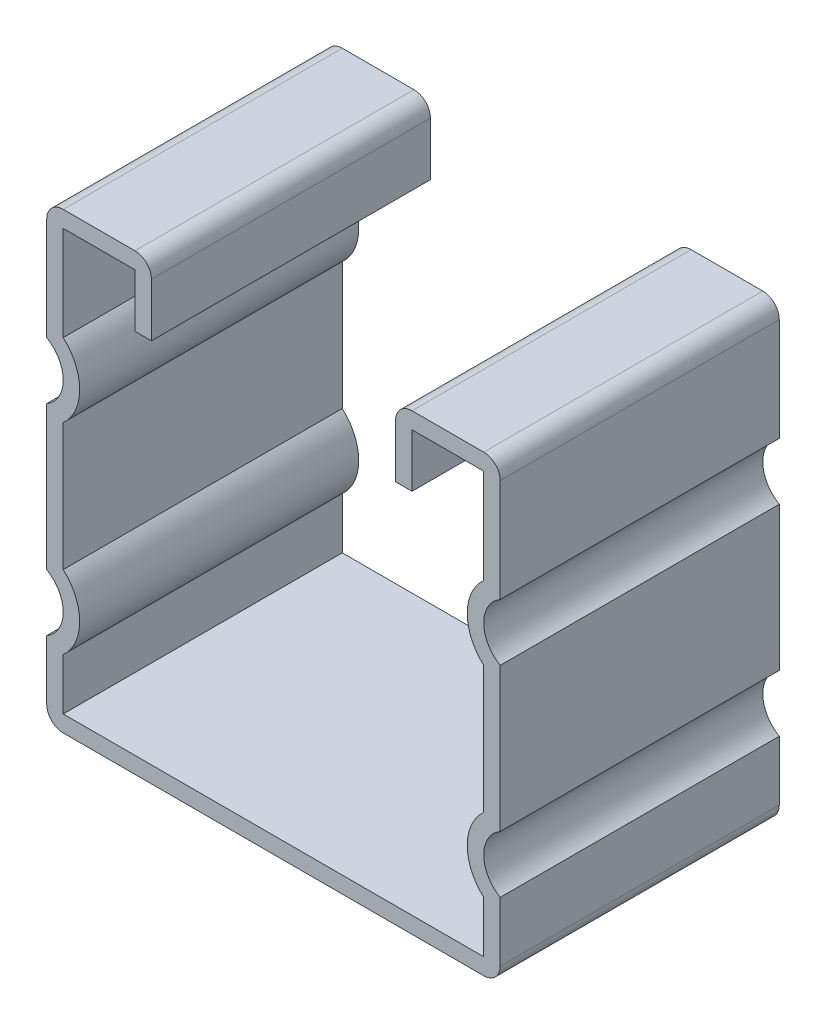
SolidWorks part; units mm, degrees
ref_plane "Plane1" through (0, 0, 0) normal (0, 0, 1) x (1, 0, 0)
ref_plane "Plane2" through (0, 0, 0) normal (0, 1, 0) x (1, 0, 0)
ref_plane "Plane3" through (0, 0, 0) normal (1, 0, 0) x (0, 0, -1)
sketch "Sketch1" plane through (0, 0, 0) normal (0, 0, 1) x (1, 0, 0)
  line L0 (-20.6375, 21.1074) -> (-20.6375, 11.7397)
  line L1 (-20.6375, 6.5483) -> (-20.6375, -6.5483)
  line L2 (-19.1389, -18.669) -> (19.1389, -18.669)
  line L3 (20.6375, -17.1704) -> (20.6375, -11.7397)
  line L4 (20.6375, 11.7397) -> (20.6375, 21.1074)
  line L5 (19.1389, 22.606) -> (12.6111, 22.606)
  line L6 (11.1125, 21.1074) -> (11.1125, 16.256)
  line L7 (-19.1389, 22.606) -> (-12.6111, 22.606)
  line L8 (-11.1125, 21.1074) -> (-11.1125, 16.256)
  line L9 (19.1389, -12.495) -> (19.1389, 12.495) construction
  line L10 (-19.1389, 12.495) -> (-19.1389, -12.495) construction
  line L11 (-12.6111, 21.1074) -> (-12.6111, 16.256)
  line L12 (-19.1389, 21.1074) -> (-12.6111, 21.1074)
  line L13 (-19.1389, 21.1074) -> (-19.1389, 12.495)
  line L14 (-19.1389, 5.793) -> (-19.1389, -5.793)
  line L15 (-19.1389, -17.1704) -> (19.1389, -17.1704)
  line L16 (19.1389, -17.1704) -> (19.1389, -12.495)
  line L17 (19.1389, 12.495) -> (19.1389, 21.1074)
  line L18 (19.1389, 21.1074) -> (12.6111, 21.1074)
  line L19 (12.6111, 21.1074) -> (12.6111, 16.256)
  line L20 (-12.6111, 16.256) -> (-11.1125, 16.256)
  line L21 (11.1125, 16.256) -> (12.6111, 16.256)
  line L22 (-10.16, 0) -> (12.7, 0) construction
  line L23 (-20.6375, -11.7397) -> (-20.6375, -17.1704)
  line L24 (-19.1389, -12.495) -> (-19.1389, -17.1704)
  line L25 (20.6375, -6.5483) -> (20.6375, 6.5483)
  line L26 (19.1389, -5.793) -> (19.1389, 5.793)
  arc A0 (20.6375, 11.7397) -> (20.6375, 6.5483) centre (22.1361, 9.144) ccw
  arc A1 (-20.6375, 6.5483) -> (-20.6375, 11.7397) centre (-22.1361, 9.144) ccw
  arc A2 (-12.6111, 22.606) -> (-11.1125, 21.1074) centre (-12.6111, 21.1074) cw
  arc A3 (-20.6375, 21.1074) -> (-19.1389, 22.606) centre (-19.1389, 21.1074) cw
  arc A4 (-19.1389, -18.669) -> (-20.6375, -17.1704) centre (-19.1389, -17.1704) cw
  arc A5 (20.6375, -17.1704) -> (19.1389, -18.669) centre (19.1389, -17.1704) cw
  arc A6 (19.1389, 22.606) -> (20.6375, 21.1074) centre (19.1389, 21.1074) cw
  arc A7 (11.1125, 21.1074) -> (12.6111, 22.606) centre (12.6111, 21.1074) cw
  arc A8 (-19.1389, 5.793) -> (-19.1389, 12.495) centre (-22.1361, 9.144) ccw
  arc A9 (19.1389, 12.495) -> (19.1389, 5.793) centre (22.1361, 9.144) ccw
  arc A10 (20.6375, -11.7397) -> (20.6375, -6.5483) centre (22.1361, -9.144) cw
  arc A11 (19.1389, -12.495) -> (19.1389, -5.793) centre (22.1361, -9.144) cw
  arc A12 (-19.1389, -5.793) -> (-19.1389, -12.495) centre (-22.1361, -9.144) cw
  arc A13 (-20.6375, -6.5483) -> (-20.6375, -11.7397) centre (-22.1361, -9.144) cw
  dimension "D9" = 2.9972
  dimension "D10" = 2.9972
  dimension "D1" = 20.6375
  dimension "Width" = 41.275
  dimension "base" = 18.669
  dimension "ToeHt" = 22.606
  dimension "D6" = 22.225
  dimension "edge" = 9.525
  dimension "Lip" = 6.35
  dimension "D2" = 9.525
  dimension "gauge" = 1.4986
extrude "Base-Extrude" add sketch "Sketch1" along normal mid plane 25.4
equation "\"D1@Sketch1\" = \"Width@Sketch1\" / 2"
equation "\"D6@Sketch1\" = \"Width@Sketch1\" - 2 * \"edge@Sketch1\""
equation "\"D10@Sketch1\" = 2 * \"gauge@Sketch1\""
equation "\"D9@Sketch1\" = \"D10@Sketch1\""
equation "\"D2@Sketch1\" = \"edge@Sketch1\""
